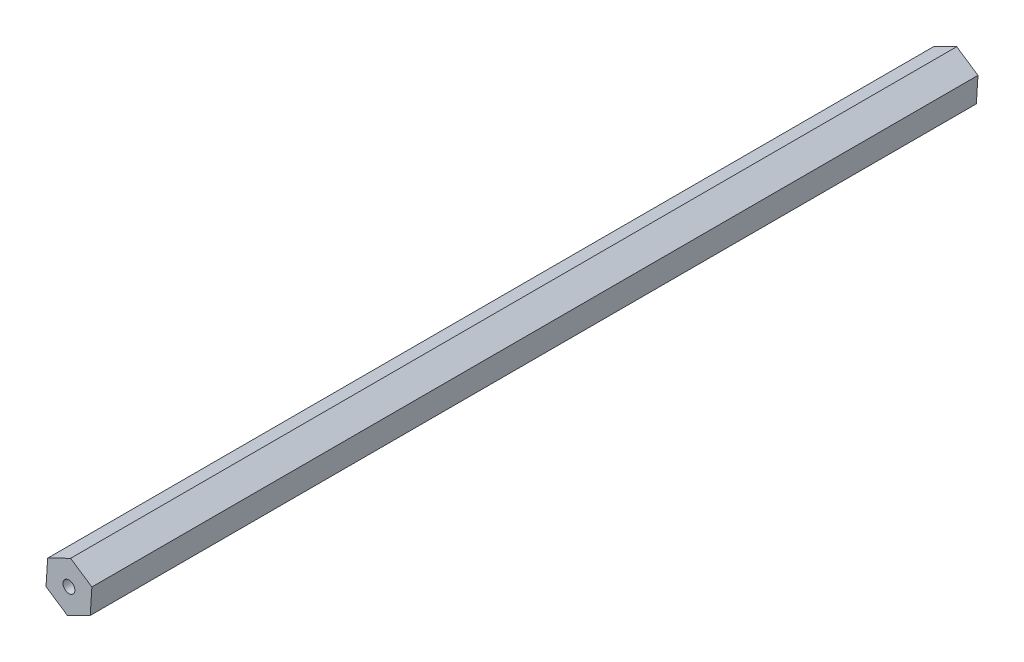
SolidWorks part; units mm, degrees
material "Cedar"
ref_plane "Front Plane" through (0, 0, 0) normal (0, 0, 1) x (1, 0, 0)
ref_plane "Top Plane" through (0, 0, 0) normal (0, 1, 0) x (1, 0, 0)
ref_plane "Right Plane" through (0, 0, 0) normal (1, 0, 0) x (0, 0, -1)
sketch "Sketch1" plane through (0, 0, 0) normal (0, 0, 1) x (1, 0, 0)
  line L0 (7.2028, -4.8083) -> (7.7655, 3.8336)
  line L1 (7.7655, 3.8336) -> (0.5627, 8.642)
  line L2 (0.5627, 8.642) -> (-7.2028, 4.8083)
  line L3 (-7.2028, 4.8083) -> (-7.7655, -3.8336)
  line L4 (-7.7655, -3.8336) -> (-0.5627, -8.642)
  line L5 (-0.5627, -8.642) -> (7.2028, -4.8083)
  circle A0 centre (0, 0) radius 2
  circle A1 centre (0, 0) radius 7.5 construction
extrude "Boss-Extrude1" add sketch "Sketch1" along normal blind 300
